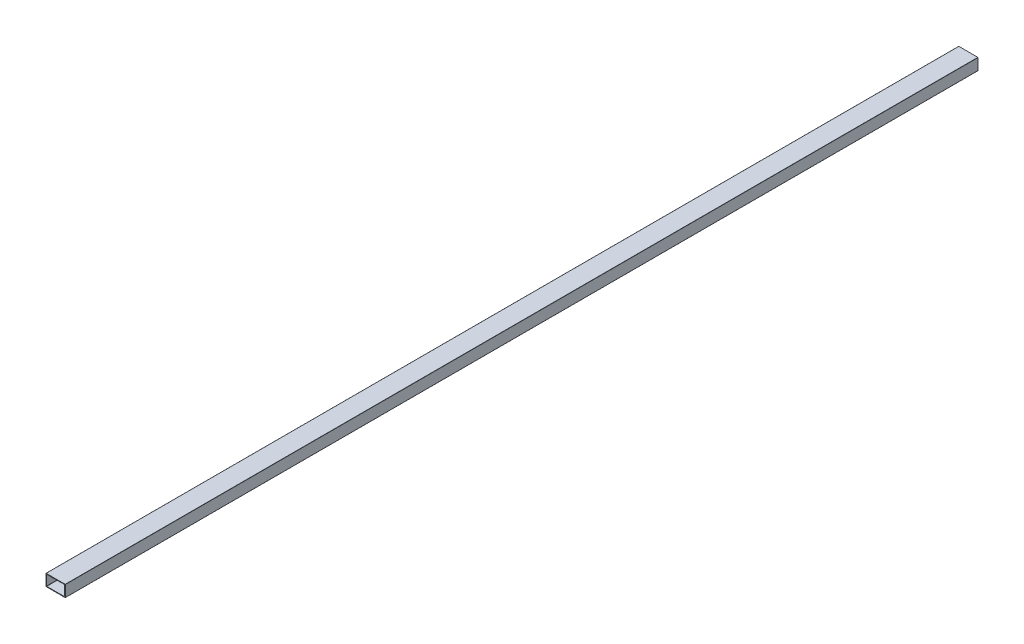
SolidWorks part; units mm, degrees
material "AISI 1035 Acero (SS)"
ref_plane "Alzado" through (0, 0, 0) normal (0, 0, 1) x (1, 0, 0)
ref_plane "Planta" through (0, 0, 0) normal (0, 1, 0) x (1, 0, 0)
ref_plane "Vista lateral" through (0, 0, 0) normal (1, 0, 0) x (0, 0, -1)
sketch "Croquis1" plane through (0, 0, 0) normal (0, 0, 1) x (1, 0, 0)
  line L0 (-59.7, -34.3) -> (-59.7, 34.3)
  line L1 (-63.5, -38.1) -> (63.5, -38.1)
  line L2 (-63.5, -38.1) -> (-63.5, 38.1)
  line L3 (-63.5, 38.1) -> (63.5, 38.1)
  line L4 (63.5, -38.1) -> (63.5, 38.1)
  line L5 (-63.5, -38.1) -> (63.5, 38.1) construction
  line L6 (-63.5, 38.1) -> (63.5, -38.1) construction
  line L7 (-59.7, 34.3) -> (59.7, 34.3)
  line L8 (59.7, -34.3) -> (59.7, 34.3)
  line L9 (-59.7, -34.3) -> (59.7, -34.3)
  point P0 (0, 0)
  dimension "D1" = 76.2
  dimension "D2" = 127
  dimension "D3" = 3.8
extrude "Saliente-Extruir1" add sketch "Croquis1" against normal blind 6000
fillet "Redondeo1" radius 1 8 edges at (-59.7, 34.3, -3000) (59.7, 34.3, -3000) (59.7, -34.3, -3000) (-63.5, -38.1, -3000) (-63.5, 38.1, -3000) (-59.7, -34.3, -3000) (63.5, -38.1, -3000) (63.5, 38.1, -3000)
